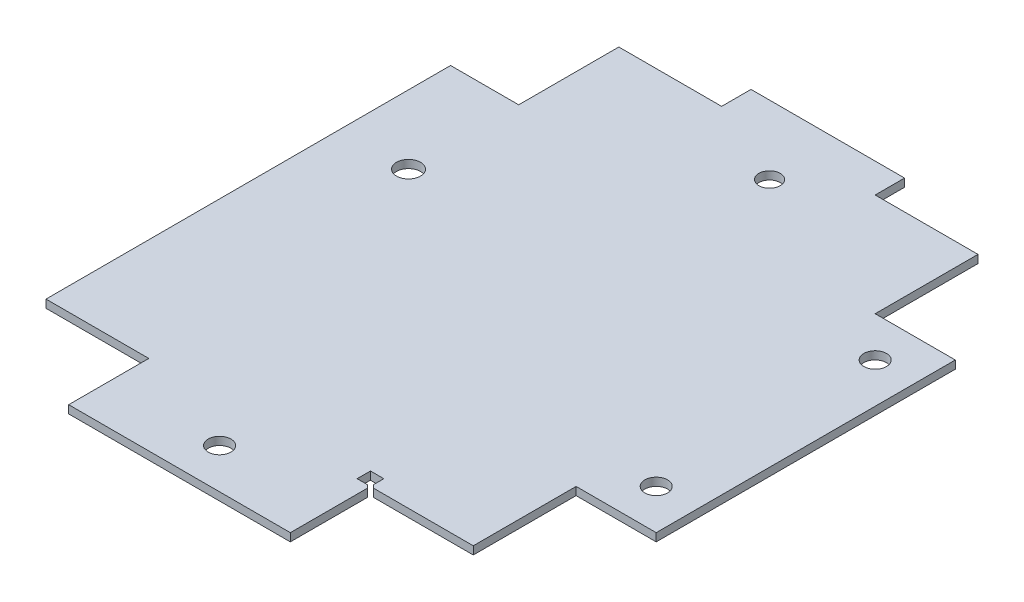
SolidWorks part; units mm, degrees
ref_plane "Alzado" through (0, 0, 0) normal (0, 0, 1) x (1, 0, 0)
ref_plane "Planta" through (0, 0, 0) normal (0, 1, 0) x (1, 0, 0)
ref_plane "Vista lateral" through (0, 0, 0) normal (1, 0, 0) x (0, 0, -1)
sketch "Croquis1" plane through (0, 0, 0) normal (0, 1, 0) x (1, 0, 0)
  line L1 (-95, 115) -> (95, 115)
  line L2 (-95, 115) -> (-95, -115)
  line L3 (-95, -115) -> (95, -115)
  line L4 (95, 115) -> (95, -115)
  line L5 (-95, 115) -> (95, -115) construction
  line L6 (-95, -115) -> (95, 115) construction
  point P0 (0, 0)
  dimension "D1" = 230
extrude "Saliente-Extruir2" add sketch "Croquis1" along normal blind 3
sketch "Croquis3" plane through (0, 3, 0) normal (0, 1, 0) x (1, 0, 0)
  line L1 (95, -115) -> (65, -115)
  line L2 (95, -115) -> (95, -85)
  line L3 (95, -85) -> (65, -85)
  line L4 (65, -115) -> (65, -85)
extrude "Cortar-Extruir1" cut sketch "Croquis3" against normal blind 10
sketch "Croquis5" plane through (0, 3, 0) normal (0, 1, 0) x (1, 0, 0)
  line L1 (65, -115) -> (26.5, -115)
  line L2 (65, -115) -> (65, -85)
  line L3 (65, -85) -> (26.5, -85)
  line L4 (26.5, -115) -> (26.5, -85)
extrude "Cortar-Extruir2" cut sketch "Croquis5" against normal blind 10
sketch "Croquis6" plane through (0, 3, 0) normal (0, 1, 0) x (1, 0, 0)
  line L1 (95, -85) -> (65, -85)
  line L2 (95, -85) -> (95, -46.5)
  line L3 (95, -46.5) -> (65, -46.5)
  line L4 (65, -85) -> (65, -46.5)
extrude "Cortar-Extruir3" cut sketch "Croquis6" against normal blind 10
sketch "Croquis7" plane through (0, 3, 0) normal (0, 1, 0) x (1, 0, 0)
  line L1 (-95, -115) -> (-56.5, -115)
  line L2 (-95, -115) -> (-95, -85)
  line L3 (-95, -85) -> (-56.5, -85)
  line L4 (-56.5, -115) -> (-56.5, -85)
extrude "Cortar-Extruir4" cut sketch "Croquis7" against normal blind 10
sketch "Croquis9" plane through (0, 3, 0) normal (0, 1, 0) x (1, 0, 0)
  line L0 (26.5, -85) -> (26.5, -85.75)
  line L1 (26.5, -85) -> (26.5, -115) construction
  line L2 (26.5, -85) -> (27.25, -85)
  line L3 (65, -85) -> (26.5, -85) construction
  line L4 (26.5, -85) -> (26.5, -84.25) construction
  line L5 (26.5, -85) -> (25.75, -85) construction
  line L6 (26.5, -85.75) -> (25.75, -85)
  line L7 (25.75, -85) -> (26.5, -84.25)
  line L8 (26.5, -84.25) -> (27.25, -85)
extrude "Cortar-Extruir12" cut sketch "Croquis9" against normal blind 10
sketch "Croquis11" plane through (0, 3, 0) normal (0, 1, 0) x (1, 0, 0)
  line L0 (65, -85) -> (27.25, -85) construction
  line L1 (21.5, -80) -> (26.5, -80)
  line L2 (21.5, -80) -> (21.5, -85)
  line L3 (21.5, -85) -> (26.5, -85)
  line L4 (26.5, -80) -> (26.5, -85)
  line L5 (21.5, -80) -> (26.5, -85) construction
  line L6 (21.5, -85) -> (26.5, -80) construction
  line L7 (26.5, -85.75) -> (26.5, -115) construction
  point P0 (24, -82.5)
  dimension "D1" = 0
  dimension "D2" = 0
extrude "Cortar-Extruir13" cut sketch "Croquis11" against normal blind 10
sketch "Croquis12" plane through (0, 3, 0) normal (0, 1, 0) x (1, 0, 0)
  line L0 (26.5, -85.75) -> (25.75, -85)
  line L1 (26.5, -85.75) -> (26.3232, -85.9268)
  line L2 (25.75, -85) -> (25.5732, -85.1768)
  line L3 (26.3232, -85.9268) -> (25.5732, -85.1768)
extrude "Cortar-Extruir14" cut sketch "Croquis12" against normal blind 10
sketch "Croquis13" plane through (0, 3, 0) normal (0, 1, 0) x (1, 0, 0)
  line L0 (26.5, -84.25) -> (27.25, -85)
  line L1 (26.5, -84.25) -> (26.6768, -84.0732)
  line L2 (27.25, -85) -> (27.4268, -84.8232)
  line L3 (26.6768, -84.0732) -> (27.4268, -84.8232)
extrude "Cortar-Extruir15" cut sketch "Croquis13" against normal blind 10
sketch "Croquis14" plane through (0, 3, 0) normal (0, 1, 0) x (1, 0, 0)
  line L0 (25.5732, -85.1768) -> (25.75, -85)
  line L1 (25.5732, -85.1768) -> (24.8254, -84.429)
  line L2 (25.75, -85) -> (25.0022, -84.2522)
  line L3 (24.8254, -84.429) -> (25.0022, -84.2522)
  line L4 (26.3232, -85.9268) -> (26.5, -85.75)
  line L5 (26.3232, -85.9268) -> (26.7373, -86.3408)
  line L6 (26.5, -85.75) -> (26.9141, -86.1641)
  line L7 (26.7373, -86.3408) -> (26.9141, -86.1641)
  line L8 (27.4268, -84.8232) -> (27.25, -85)
  line L9 (27.4268, -84.8232) -> (27.7759, -85.1723)
  line L10 (27.25, -85) -> (27.5991, -85.3491)
  line L11 (27.7759, -85.1723) -> (27.5991, -85.3491)
  line L12 (26.6768, -84.0732) -> (26.5, -84.25)
  line L13 (26.6768, -84.0732) -> (26.2537, -83.6502)
  line L14 (26.5, -84.25) -> (26.0769, -83.8269)
  line L15 (26.2537, -83.6502) -> (26.0769, -83.8269)
extrude "Cortar-Extruir16" cut sketch "Croquis14" against normal blind 10
sketch "Croquis15" plane through (0, 3, 0) normal (0, 1, 0) x (1, 0, 0)
  line L0 (95, 115) -> (95, 76.5)
  line L1 (95, 115) -> (65, 115)
  line L2 (95, 76.5) -> (65, 76.5)
  line L3 (65, 115) -> (65, 76.5)
  line L4 (95, -46.5) -> (95, 115) construction
extrude "Cortar-Extruir17" cut sketch "Croquis15" against normal blind 10
sketch "Croquis16" plane through (0, 3, 0) normal (0, 1, 0) x (1, 0, 0)
  line L1 (-95, 115) -> (-69.5, 115)
  line L2 (-95, 115) -> (-95, 66.5)
  line L3 (-95, 66.5) -> (-69.5, 66.5)
  line L4 (-69.5, 115) -> (-69.5, 66.5)
extrude "Cortar-Extruir18" cut sketch "Croquis16" against normal blind 10
sketch "Croquis17" plane through (0, 3, 0) normal (0, 1, 0) x (1, 0, 0)
  line L0 (-95, 66.5) -> (-95, -85) construction
  line L1 (-69.5, 115) -> (-45.5, 115)
  line L2 (-69.5, 115) -> (-69.5, 104)
  line L3 (-69.5, 104) -> (-45.5, 104)
  line L4 (-45.5, 115) -> (-45.5, 104)
  point P7 (-45.5, 109.5)
  dimension "D1" = 49.5
  dimension "D2" = 11
extrude "Cortar-Extruir19" cut sketch "Croquis17" against normal blind 10
sketch "Croquis18" plane through (0, 3, 0) normal (0, 1, 0) x (1, 0, 0)
  line L0 (65, 115) -> (-45.5, 115) construction
  line L1 (-45.5, 104) -> (-31, 104)
  line L2 (-45.5, 104) -> (-45.5, 115)
  line L3 (-45.5, 115) -> (-31, 115)
  line L4 (-31, 104) -> (-31, 115)
  line L5 (-69.5, 66.5) -> (-69.5, 104) construction
  dimension "D1" = 38.5
extrude "Cortar-Extruir20" cut sketch "Croquis18" against normal blind 10
sketch "Croquis19" plane through (0, 3, 0) normal (0, 1, 0) x (1, 0, 0)
  line L0 (95, -46.5) -> (95, 76.5) construction
  line L1 (65, 76.5) -> (95, 76.5) construction
  line L2 (95, -46.5) -> (65, -46.5) construction
  circle A0 centre (80, 61.5) radius 4.25
  circle A1 centre (80, -31.5) radius 4.25
  dimension "D1" = 15
  dimension "D2" = 15
  dimension "D3" = 15
  dimension "D4" = 15
extrude "Cortar-Extruir21" cut sketch "Croquis19" against normal blind 10
sketch "Croquis20" plane through (0, 3, 0) normal (0, 1, 0) x (1, 0, 0)
  line L0 (-56.5, -115) -> (26.5, -115) construction
  line L1 (-56.5, -115) -> (-56.5, -85) construction
  circle A0 centre (-15, -100) radius 4.25
  dimension "D1" = 15
  dimension "D2" = 41.5
extrude "Cortar-Extruir22" cut sketch "Croquis20" against normal blind 10
sketch "Croquis21" plane through (0, 3, 0) normal (0, 1, 0) x (1, 0, 0)
  line L0 (-95, 66.5) -> (-95, -85) construction
  line L1 (-56.5, -115) -> (26.5, -115) construction
  circle A0 centre (-69.25, 25) radius 4.5
  dimension "D1" = 25.75
  dimension "D2" = 9
  dimension "D3" = 140
extrude "Cortar-Extruir23" cut sketch "Croquis21" against normal blind 10
sketch "Croquis22" plane through (0, 3, 0) normal (0, 1, 0) x (1, 0, 0)
  line L0 (95, -46.5) -> (95, 76.5) construction
  line L1 (65, 115) -> (-31, 115) construction
  circle A0 centre (1.7, 89.25) radius 4
  dimension "D1" = 93.3
  dimension "D2" = 25.75
extrude "Cortar-Extruir24" cut sketch "Croquis22" against normal blind 10
sketch "Croquis23" plane through (0, 3, 0) normal (0, 1, 0) x (1, 0, 0)
  line L0 (65, 115) -> (65, 76.5) construction
  line L1 (65, 104) -> (95, 104)
  line L2 (65, 104) -> (65, 65.5)
  line L3 (65, 65.5) -> (95, 65.5)
  line L4 (95, 104) -> (95, 65.5)
extrude "Cortar-Extruir25" cut sketch "Croquis23" against normal blind 10
sketch "Croquis24" plane through (0, 3, 0) normal (0, 1, 0) x (1, 0, 0)
  line L0 (81.4361, 65.5) -> (95, 65.5) construction
  circle A0 centre (80, 50.5) radius 4.25
  dimension "D1" = 15
extrude "Cortar-Extruir26" cut sketch "Croquis24" against normal blind 10
sketch "Croquis25" plane through (0, 3, 0) normal (0, 1, 0) x (1, 0, 0)
  line L0 (78.5639, 65.5) -> (81.4361, 65.5)
  circle A0 centre (80, 61.5) radius 4.25
  arc M25 (81.4361, 65.5) -> (78.5639, 65.5) centre (80, 61.5) cw
extrude "Saliente-Extruir4" add sketch "Croquis25" against normal blind 3 contours L0 M25
sketch "Croquis26" plane through (0, 3, 0) normal (0, 1, 0) x (1, 0, 0)
  line L1 (65, 115) -> (26.5, 115)
  line L2 (65, 115) -> (65, 104)
  line L3 (65, 104) -> (26.5, 104)
  line L4 (26.5, 115) -> (26.5, 104)
extrude "Cortar-Extruir27" cut sketch "Croquis26" against normal blind 30
